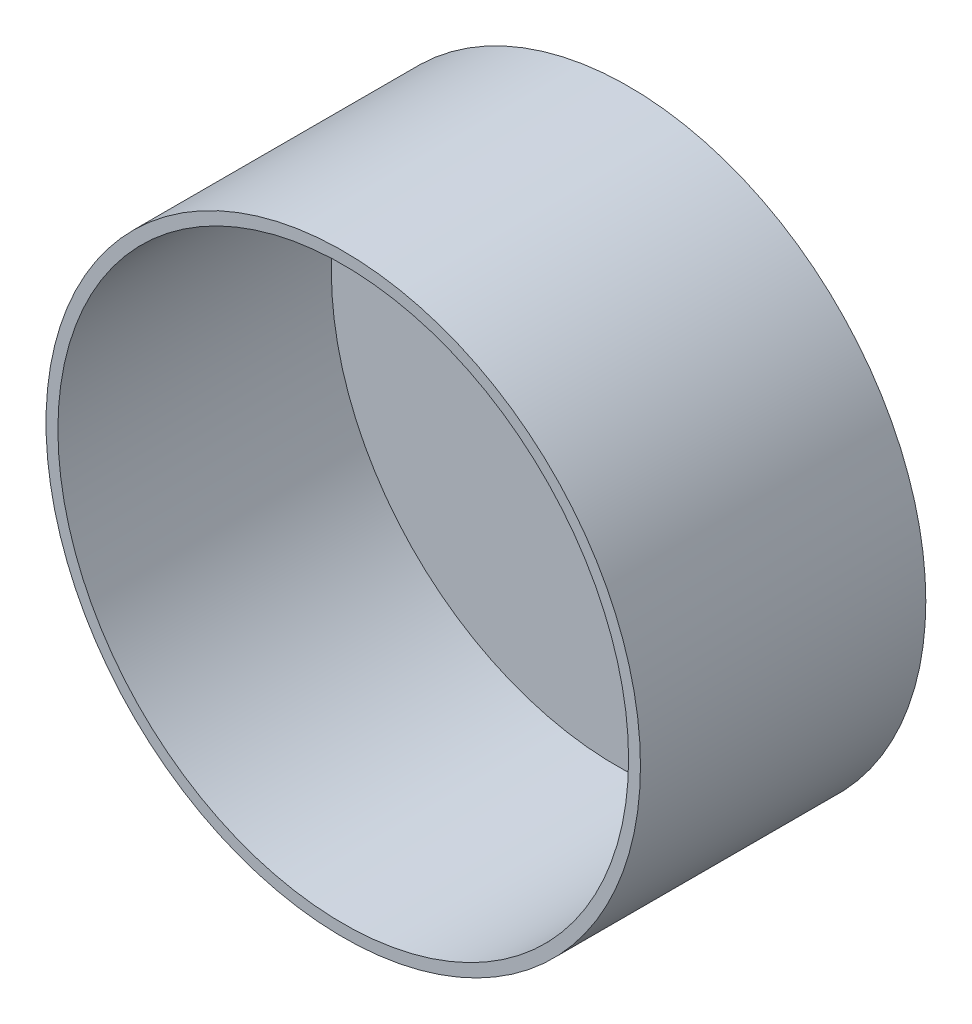
SolidWorks part; units mm, degrees
ref_plane "Front Plane" through (0, 0, 0) normal (0, 0, 1) x (1, 0, 0)
ref_plane "Top Plane" through (0, 0, 0) normal (0, 1, 0) x (1, 0, 0)
ref_plane "Right Plane" through (0, 0, 0) normal (1, 0, 0) x (0, 0, -1)
sketch "Outer Diameter Sketch" plane through (0, 0, 0) normal (0, 0, 1) x (1, 0, 0)
  circle A0 centre (0, 0) radius 125
  dimension "D1" = 250
extrude "Outer Diameter Extrude" add sketch "Outer Diameter Sketch" along normal blind 120
sketch "Inner Diameter Sketch" plane through (0, 0, 120) normal (0, 0, 1) x (1, 0, 0)
  circle A0 centre (0, 0) radius 120
  circle A1 centre (0, 0) radius 125 construction
extrude "Inner Diameter Cut" cut sketch "Inner Diameter Sketch" against normal offset from surface (115 mm away) 5 up to face at (125, 0, 0)
